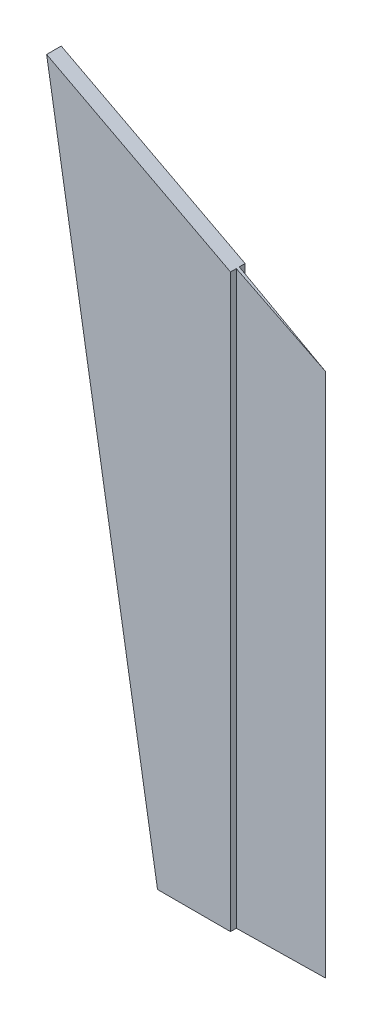
SolidWorks part; units mm, degrees
ref_plane "前视基准面" through (0, 0, 0) normal (0, 0, 1) x (1, 0, 0)
ref_plane "上视基准面" through (0, 0, 0) normal (0, 1, 0) x (1, 0, 0)
ref_plane "右视基准面" through (0, 0, 0) normal (1, 0, 0) x (0, 0, -1)
sketch "草图1" plane through (0, 0, 0) normal (0, 0, 1) x (1, 0, 0)
  line L0 (-7.2591, -114.3814) -> (-45.2493, 114.3814)
  line L1 (-45.2493, 114.3814) -> (47.7409, 65.6186)
  line L2 (47.7409, 65.6186) -> (47.7409, -114.3814)
  line L3 (47.7409, -114.3814) -> (-7.2591, -114.3814)
  dimension "D1" = 55
  dimension "D2" = 228.7629
  dimension "D3" = 105
  dimension "D4" = 180
  dimension "D5" = 90
extrude "凸台-拉伸1" add sketch "草图1" along normal blind 5
sketch "草图2" plane through (0, -114.3814, 0) normal (0, -1, 0) x (1, 0, 0)
  line L0 (47.7409, 2.5) -> (51.2494, 2.5) construction
  line L1 (47.7409, 5) -> (47.7409, 0) construction
  line L2 (17.7409, 5) -> (47.7409, 5.3621)
  line L3 (17.7409, 3.0004) -> (17.7409, 5)
  line L4 (17.7409, 0) -> (17.7409, 1.9996)
  line L5 (47.7409, 0) -> (-45.2493, 0) construction
  line L6 (47.7409, 5) -> (-45.2493, 5) construction
  line L7 (17.7409, 1.9996) -> (47.7409, 2.5)
  line L8 (17.7409, 3.0004) -> (47.7409, 2.5)
  line L9 (47.7409, 5) -> (47.7409, 0) construction
  line L10 (47.7409, 5.3621) -> (52.1307, 0.9722)
  line L11 (47.7409, -0.8139) -> (17.7409, 0)
  line L12 (52.1307, 0.9722) -> (47.7409, -0.8139)
  line L13 (47.7409, 2.5) -> (15.9032, 2.5) construction
  line L14 (17.7409, 32.5) -> (55.875, 32.5) construction
  line L15 (47.7409, 35.3621) -> (52.1307, 30.9722)
  line L16 (17.7409, 33.0004) -> (47.7409, 32.5)
  line L17 (47.7409, 29.1861) -> (17.7409, 30)
  line L18 (17.7409, 31.9996) -> (47.7409, 32.5)
  line L19 (17.7409, 35) -> (47.7409, 35.3621)
  line L20 (17.7409, 33.0004) -> (17.7409, 35)
  line L21 (52.1307, 30.9722) -> (47.7409, 29.1861)
  line L22 (17.7409, 30) -> (17.7409, 31.9996)
  dimension "D1" = 30
  dimension "D2" = 30
extrude "切除-拉伸2" cut sketch "草图2" against normal blind 200
